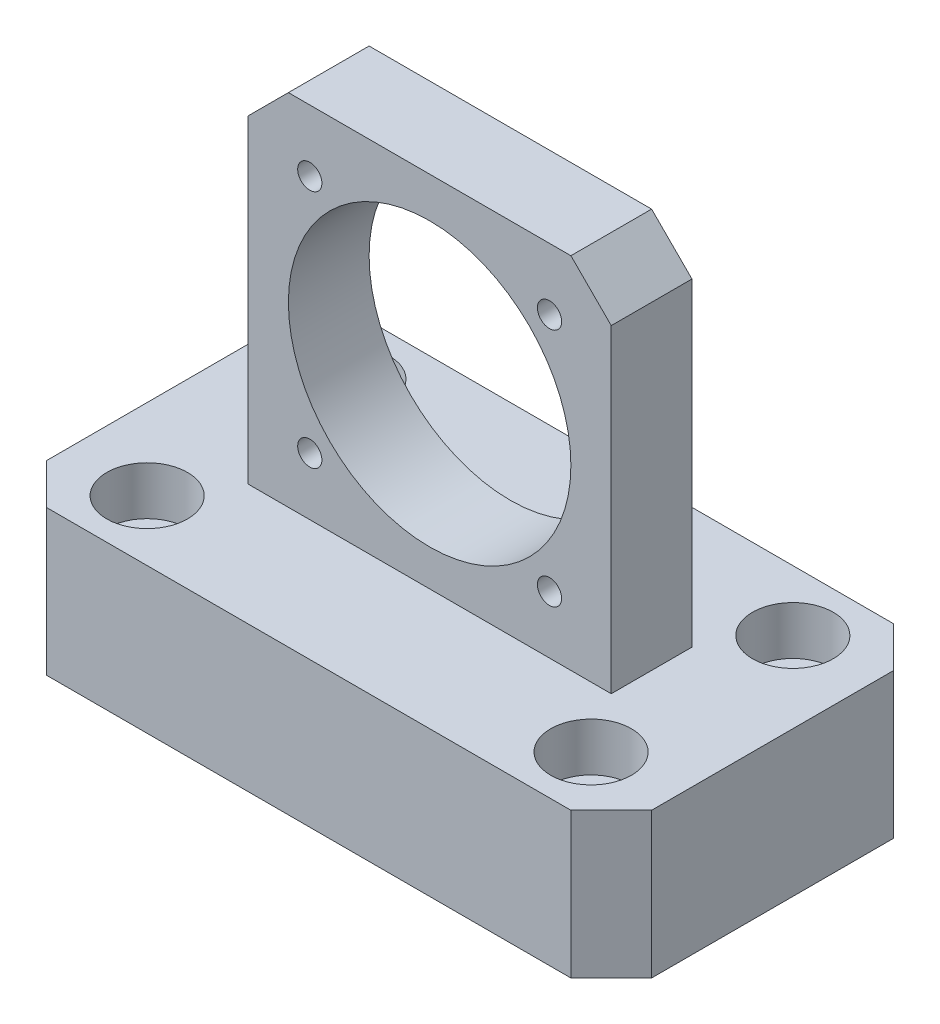
SolidWorks part; units mm, degrees
ref_plane "정면" through (0, 0, 0) normal (0, 0, 1) x (1, 0, 0)
ref_plane "윗면" through (0, 0, 0) normal (0, 1, 0) x (1, 0, 0)
ref_plane "우측면" through (0, 0, 0) normal (1, 0, 0) x (0, 0, -1)
sketch "스케치1" plane through (0, 0, 0) normal (0, 1, 0) x (1, 0, 0)
  line L1 (0, 0) -> (75, 0)
  line L2 (0, 0) -> (0, 40)
  line L3 (0, 40) -> (75, 40)
  line L4 (75, 0) -> (75, 40)
  dimension "D1" = 75
  dimension "D2" = 40
extrude "보스-돌출1" add sketch "스케치1" along normal blind 18
chamfer "모따기1" distance 5 angle 45 4 edges at (0, 9, -40) (75, 9, -40) (0, 9, 0) (75, 9, 0)
sketch "스케치2" plane through (0, 18, 0) normal (0, 1, 0) x (1, 0, 0)
  line L0 (0, 35) -> (0, 5) construction
  line L1 (15, 25) -> (60, 25)
  line L2 (15, 25) -> (15, 15)
  line L3 (15, 15) -> (60, 15)
  line L4 (60, 25) -> (60, 15)
  line L5 (5, 0) -> (70, 0) construction
  dimension "D1" = 15
  dimension "D2" = 45
  dimension "D3" = 10
  dimension "D4" = 15
extrude "보스-돌출2" add sketch "스케치2" along normal blind 44.5
chamfer "모따기2" distance 5 angle 45 2 edges at (15, 62.5, -20) (60, 62.5, -20)
sketch "스케치3" plane through (0, 0, -15) normal (0, 0, 1) x (1, 0, 0)
  line L0 (37.5, 62.5) -> (37.5, 0) construction
  line L1 (20, 62.5) -> (55, 62.5) construction
  line L2 (5, 0) -> (70, 0) construction
  circle A0 centre (37.5, 40) radius 17.5
  dimension "D1" = 35
  dimension "D2" = 40
extrude "컷-돌출1" cut sketch "스케치3" against normal through all
sketch "스케치4" plane through (0, 0, -15) normal (0, 0, 1) x (1, 0, 0)
  line L1 (22.65, 54.85) -> (52.35, 54.85) construction
  line L2 (22.65, 54.85) -> (22.65, 25.15) construction
  line L3 (22.65, 25.15) -> (52.35, 25.15) construction
  line L4 (52.35, 54.85) -> (52.35, 25.15) construction
  line L5 (22.65, 54.85) -> (52.35, 25.15) construction
  line L6 (22.65, 25.15) -> (52.35, 54.85) construction
  circle A0 centre (22.65, 54.85) radius 1.5
  circle A1 centre (52.35, 54.85) radius 1.5
  circle A2 centre (52.35, 25.15) radius 1.5
  circle A3 centre (22.65, 25.15) radius 1.5
  point P0 (37.5, 40)
  dimension "D3" = 3
  dimension "D1" = 29.7
  dimension "D2" = 29.7
extrude "컷-돌출2" cut sketch "스케치4" against normal through all
sketch "스케치5" plane through (0, 18, 0) normal (0, 1, 0) x (1, 0, 0)
  line L0 (5, 0) -> (70, 0) construction
  line L1 (0, 35) -> (0, 5) construction
  circle A0 centre (10, 32.5) radius 5
  circle A1 centre (10, 7.5) radius 5
  circle A2 centre (65, 7.5) radius 5
  circle A3 centre (65, 32.5) radius 5
  point P8 (0, 0)
  point P9 (0, 0)
  point P10 (0, 0)
  point P11 (0, 0)
  dimension "D1" = 10
  dimension "D2" = 7.5
  dimension "D3" = 25
  dimension "D4" = 10
  dimension "D5" = 55
extrude "컷-돌출3" cut sketch "스케치5" against normal blind 6
sketch "스케치6" plane through (0, 12, 0) normal (0, 1, 0) x (1, 0, 0)
  circle A0 centre (10, 7.5) radius 2.75
  circle A1 centre (10, 32.5) radius 2.75
  circle A3 centre (65, 7.5) radius 2.75
  circle A4 centre (65, 32.5) radius 2.75
  dimension "D1" = 5.5
extrude "컷-돌출4" cut sketch "스케치6" against normal through all
